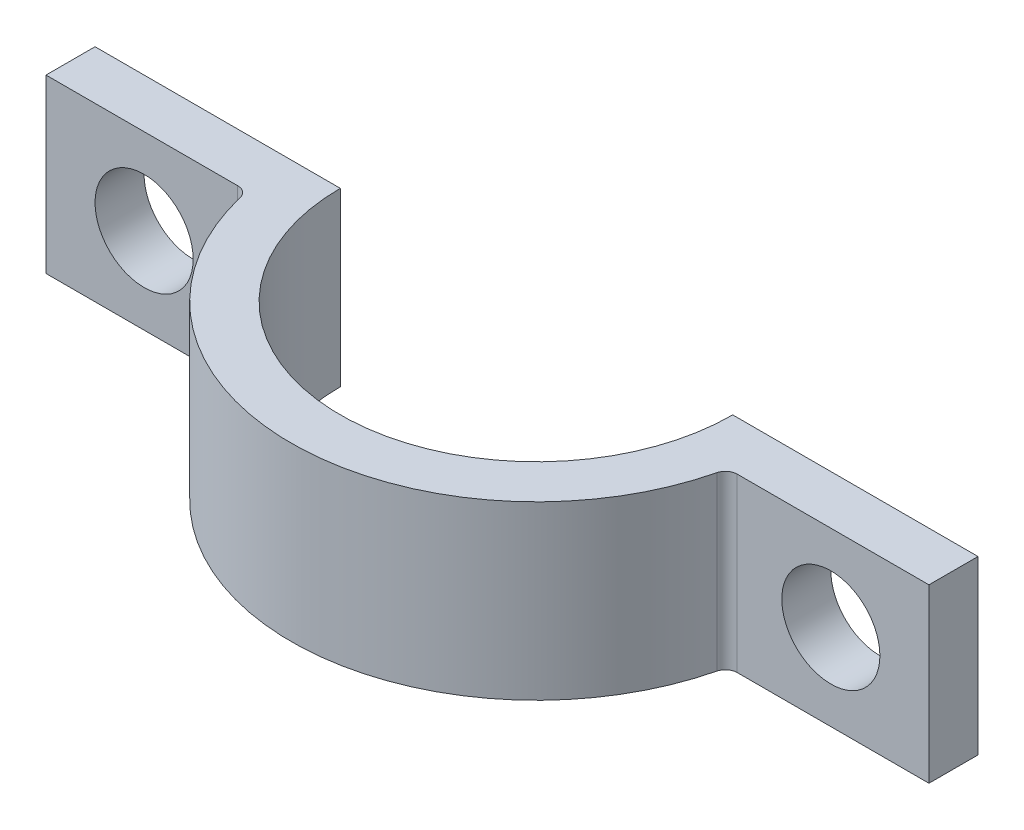
SolidWorks part; units mm, degrees
material "6061-T6 (SS)"
ref_plane "X-Y Datum" through (0, 0, 0) normal (0, 0, 1) x (1, 0, 0)
ref_plane "X-Z Datum" through (0, 0, 0) normal (0, 1, 0) x (1, 0, 0)
ref_plane "Y-Z Datum" through (0, 0, 0) normal (1, 0, 0) x (0, 0, -1)
sketch "Sketch1" plane through (0, 0, 0) normal (0, 1, 0) x (1, 0, 0)
  line L0 (-12.7, 0) -> (-28.575, 0)
  line L1 (-28.575, 0) -> (-28.575, -3.175)
  line L2 (-28.575, -3.175) -> (-16.1645, -3.175)
  line L3 (12.7, 0) -> (28.575, 0)
  line L4 (28.575, 0) -> (28.575, -3.175)
  line L5 (28.575, -3.175) -> (16.1645, -3.175)
  arc A0 (-12.7, 0) -> (12.7, 0) centre (0, 0) ccw
  arc A1 (-15.4241, -3.7567) -> (15.4241, -3.7567) centre (0, 0) ccw
  arc A2 (15.4241, -3.7567) -> (16.1645, -3.175) centre (16.1645, -3.937) cw
  arc A3 (-15.875, 0) -> (15.875, 0) centre (0, 0) ccw construction
  arc A4 (-15.4241, -3.7567) -> (-16.1645, -3.175) centre (-16.1645, -3.937) ccw
  dimension "D1" = 3.175
  dimension "D3" = 12.7
  dimension "D5" = 0.762
  dimension "D2" = 3.175
  dimension "D4" = 57.15
extrude "Boss-Extrude1" add sketch "Sketch1" along normal mid plane 11.1252
sketch "Sketch2" plane through (0, 0, 3.175) normal (0, 0, 1) x (1, 0, 0)
  line L0 (-28.575, 5.5626) -> (-16.1645, 5.5626) construction
  line L1 (-22.225, 0) -> (22.225, 0) construction
  circle A0 centre (-22.225, 0) radius 3.175
  circle A1 centre (22.225, 0) radius 3.175
  point P6 (0, 0)
  dimension "D1" = 5.5626
  dimension "D3" = 6.35
  dimension "D2" = 22.225
extrude "Cut-Extrude1" cut sketch "Sketch2" against normal through all
fillet "Fillet1" [suppressed] radius 3.81
fillet "Fillet2" [suppressed] radius 0.254
